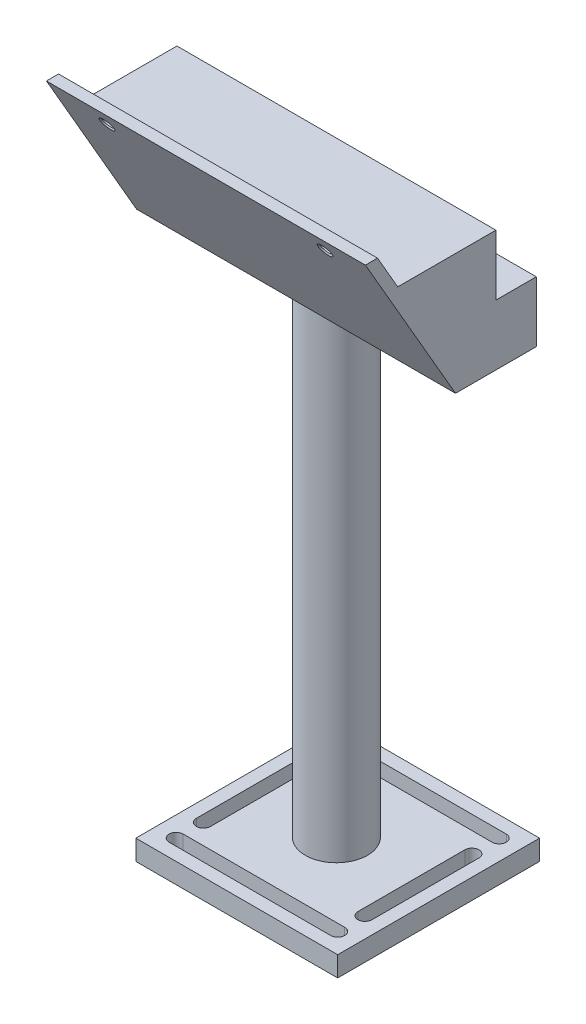
SolidWorks part; units mm, degrees
ref_plane "前视基准面" through (0, 0, 0) normal (0, 0, 1) x (1, 0, 0)
ref_plane "上视基准面" through (0, 0, 0) normal (0, 1, 0) x (1, 0, 0)
ref_plane "右视基准面" through (0, 0, 0) normal (1, 0, 0) x (0, 0, -1)
other "Configuration Table"
sketch "草图1" plane through (0, 0, 0) normal (0, 0, 1) x (1, 0, 0)
  line L0 (0, 30) -> (0, 20) construction
  line L1 (0, 0) -> (79, 0)
  line L2 (0, 0) -> (0, 30)
  line L3 (0, 30) -> (79, 30)
  line L4 (79, 0) -> (79, 30)
  line L5 (0, 20) -> (12.5, 20) construction
  line L6 (39.5, 30) -> (39.5, 0) construction
  dimension "D4" = 30
  dimension "D1" = 79
  dimension "D2" = 10
  dimension "D3" = 12.5
extrude "凸台-拉伸2" add sketch "草图1" along normal blind 10 contours L3 L4 L1 L2
sketch "草图9" plane through (0, 0, 0) normal (0, 0, -1) x (-1, 0, 0)
  line L0 (-79, 0) -> (-79, 30) construction
  line L1 (-79, 15) -> (0, 15)
  line L2 (-79, 15) -> (-79, 0)
  line L3 (-79, 0) -> (0, 0)
  line L4 (0, 15) -> (0, 0)
extrude "凸台-拉伸3" add sketch "草图9" along normal blind 10
sketch "草图10" plane through (0, 0, 0) normal (0, -1, 0) x (1, 0, 0)
  line L0 (0, 0) -> (79, 0) construction
  line L1 (0, 10) -> (0, -10) construction
  line L2 (79, 10) -> (79, -10) construction
  line L3 (39.5, 10) -> (39.5, -10) construction
  line L4 (0, 10) -> (79, 10) construction
  line L5 (79, -10) -> (0, -10) construction
  circle A0 centre (39.5, 0) radius 7.7017
extrude "凸台-拉伸4" add sketch "草图10" along normal blind 120
sketch "草图11" plane through (0, -120, 0) normal (0, -1, 0) x (1, 0, 0)
  line L0 (39.8135, 0) -> (39.8135, 25) construction
  line L1 (39.8135, 25) -> (14.8135, 25) construction
  line L3 (14.8135, 25) -> (64.8135, 25)
  line L4 (14.8135, 25) -> (14.8135, -25)
  line L5 (14.8135, -25) -> (64.8135, -25)
  line L6 (64.8135, 25) -> (64.8135, -25)
  dimension "D1" = 25
  dimension "D2" = 25
  dimension "D3" = 50
  dimension "D4" = 50
extrude "凸台-拉伸5" add sketch "草图11" along normal blind 5 contours L3 L6 L5 L4
sketch "草图12" plane through (0, -125, 0) normal (0, -1, 0) x (1, 0, 0)
  line L0 (14.8135, 25) -> (14.8135, 20) construction
  line L1 (14.8135, 25) -> (14.8135, -25) construction
  line L2 (14.8135, 20) -> (19.8135, 20) construction
  line L3 (64.8135, 20) -> (59.8135, 20) construction
  line L4 (64.8135, 25) -> (64.8135, -25) construction
  line L5 (19.8135, 20) -> (59.8135, 20) construction
  line L6 (19.8135, 21.75) -> (59.8135, 21.75)
  line L7 (19.8135, 18.25) -> (59.8135, 18.25)
  line L8 (14.8135, 0) -> (64.8135, 0) construction
  line L9 (19.8135, -20) -> (59.8135, -20) construction
  line L10 (19.8135, -21.75) -> (59.8135, -21.75)
  line L11 (19.8135, -18.25) -> (59.8135, -18.25)
  line L12 (19.8135, 18.25) -> (19.8135, 13.25) construction
  line L13 (19.8135, -18.25) -> (19.8135, -13.25) construction
  line L14 (19.8135, 13.25) -> (19.8135, -13.25) construction
  line L15 (21.5635, 13.25) -> (21.5635, -13.25)
  line L16 (18.0635, 13.25) -> (18.0635, -13.25)
  line L17 (39.8135, 25) -> (39.8135, -25) construction
  line L18 (14.8135, 25) -> (64.8135, 25) construction
  line L19 (14.8135, -25) -> (64.8135, -25) construction
  line L20 (59.8135, 13.25) -> (59.8135, -13.25) construction
  line L21 (58.0635, 13.25) -> (58.0635, -13.25)
  line L22 (61.5635, 13.25) -> (61.5635, -13.25)
  arc A0 (19.8135, 21.75) -> (19.8135, 18.25) centre (19.8135, 20) ccw
  arc A1 (59.8135, 18.25) -> (59.8135, 21.75) centre (59.8135, 20) ccw
  arc A2 (19.8135, -21.75) -> (19.8135, -18.25) centre (19.8135, -20) cw
  arc A3 (59.8135, -18.25) -> (59.8135, -21.75) centre (59.8135, -20) cw
  arc A4 (21.5635, 13.25) -> (18.0635, 13.25) centre (19.8135, 13.25) ccw
  arc A5 (18.0635, -13.25) -> (21.5635, -13.25) centre (19.8135, -13.25) ccw
  arc A6 (58.0635, 13.25) -> (61.5635, 13.25) centre (59.8135, 13.25) cw
  arc A7 (61.5635, -13.25) -> (58.0635, -13.25) centre (59.8135, -13.25) cw
  point P10 (39.8135, 20)
  point P20 (39.8135, -20)
  point P29 (19.8135, 0)
  point P42 (59.8135, 0)
  dimension "D4" = 5
  dimension "D1" = 5
  dimension "D2" = 5
  dimension "D3" = 5
  dimension "D5" = 5
extrude "切除-拉伸1" cut sketch "草图12" against normal blind 10
sketch "草图13" plane through (79, 0, 0) normal (1, 0, 0) x (0, 0, -1)
  line L0 (-10, 0) -> (-27.3205, 30)
  line L1 (-10, 30) -> (-27.3205, 30)
  line L2 (-10, 30) -> (-10, 0)
extrude "凸台-拉伸6" add sketch "草图13" against normal blind 79
sketch "草图16" plane through (79, 0, 0) normal (1, 0, 0) x (0, 0, -1)
  line L1 (-27.3205, 30) -> (-32.3205, 38.6603)
  line L2 (-27.3205, 30) -> (0, 30) construction
  line L3 (-27.3205, 30) -> (-24.3205, 30)
  line L4 (-32.3205, 38.6603) -> (-29.3205, 38.6603)
  line L5 (-29.3205, 38.6603) -> (-24.3205, 30)
  dimension "D1" = 3
  dimension "D2" = 3
extrude "凸台-拉伸7" add sketch "草图16" against normal blind 79
sketch "草图17" plane through (0, -4.3301, 7.5) normal (0, -0.5, 0.866) x (1, 0, 0)
  line L0 (0, 49.641) -> (0, 44.641) construction
  line L1 (0, 49.641) -> (0, 5) construction
  line L2 (0, 44.641) -> (12.5, 44.641) construction
  line L3 (39.5, 49.641) -> (39.5, 5) construction
  line L4 (0, 49.641) -> (79, 49.641) construction
  line L5 (0, 5) -> (79, 5) construction
  circle A0 centre (12.5, 44.641) radius 1.75
  circle A1 centre (66.5, 44.641) radius 1.75
  point P6 (12.5, 44.641)
  point P13 (66.5, 44.641)
  point P19 (12.5, 44.641)
  dimension "D1" = 5
  dimension "D2" = 12.5
hole_wizard "M3.5 螺纹孔1" positions "草图17" profile "草图18" tap size "M3.5" standard "GB" end condition through all
sketch "草图18" plane through (12.5, 34.3301, 29.8205) normal (1, 0, 0) x (0, -0.866, -0.5)
  line L0 (0, 0) -> (0, 36.6506)
  line L1 (0, 36.6506) -> (1.45, 36.6506)
  line L2 (1.45, 36.6506) -> (1.45, 0.325)
  line L3 (1.45, 0.325) -> (1.775, 0)
  line L5 (1.775, 0) -> (0, 0)
  line L6 (-1.45, 0.325) -> (-1.775, 0) construction
  line L11 (0, -6.35) -> (0, 107.95) construction
  dimension "通孔螺纹孔钻头直径" = 2.9
  dimension "通孔螺纹孔钻头深度" = 36.6506
  dimension "近端锥形沉头孔直径" = 3.55
  dimension "近端锥形沉头孔角度" = 90
cosmetic thread "孔螺蚊线1" parameters "D2"=3.5
cosmetic thread "孔螺蚊线2" parameters "D2"=3.5
